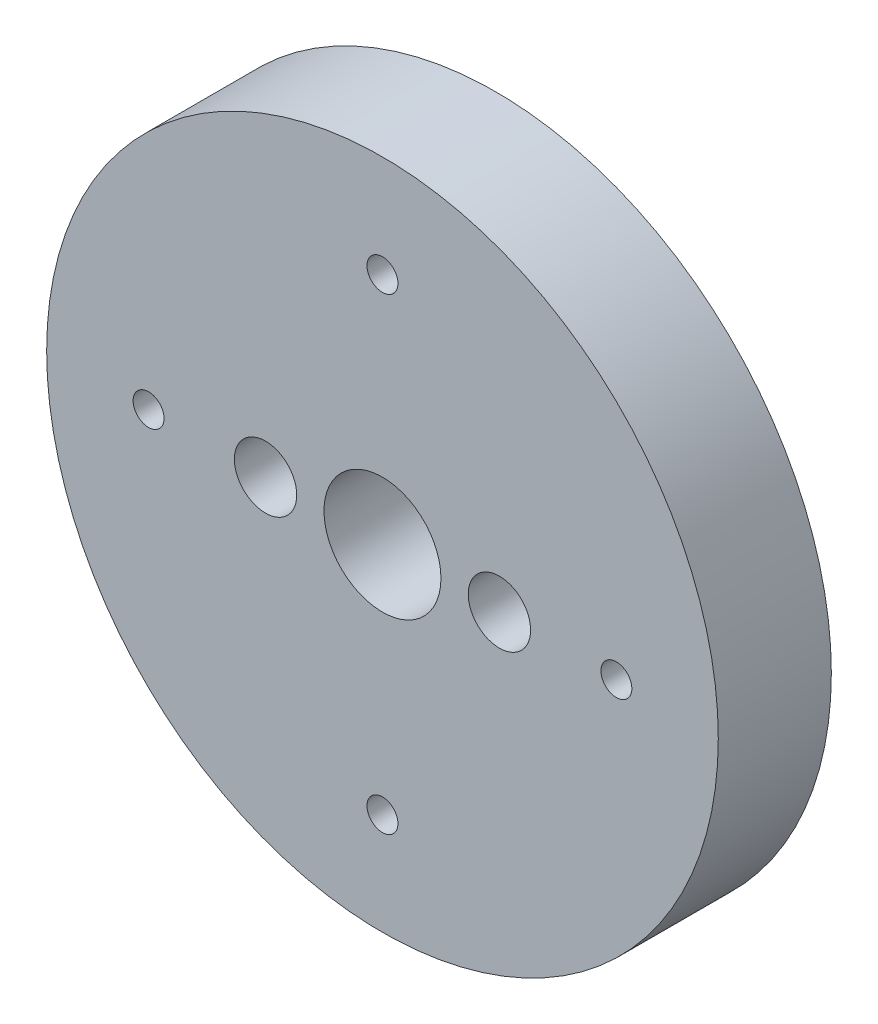
SolidWorks part; units mm, degrees
material "Balsa"
ref_plane "Front Plane" through (0, 0, 0) normal (0, 0, 1) x (1, 0, 0)
ref_plane "Top Plane" through (0, 0, 0) normal (0, 1, 0) x (1, 0, 0)
ref_plane "Right Plane" through (0, 0, 0) normal (1, 0, 0) x (0, 0, -1)
sketch "Sketch1" plane through (0, 0, 0) normal (0, 0, 1) x (1, 0, 0)
  circle A0 centre (0, 0) radius 3
  circle A1 centre (0, 0) radius 17.2292
  dimension "D1" = 6
  dimension "D2" = 34.4583
extrude "Boss-Extrude1" add sketch "Sketch1" along normal blind 5.8
sketch "Sketch2" plane through (0, 0, 5.8) normal (0, 0, 1) x (1, 0, 0)
  line L0 (0, 0) -> (0, 17.2292) construction
  circle A0 centre (0, 0) radius 17.2292 construction
  circle A1 centre (0, 12) radius 0.7937
  circle A2 centre (12, 0) radius 0.7937
  circle A3 centre (0, -12) radius 0.7937
  circle A4 centre (-12, 0) radius 0.7937
  circle A5 centre (0, 0) radius 12 construction
  dimension "D1" = 1.5875
  dimension "D2" = 12
  dimension "D3" = 4
extrude "Cut-Extrude1" cut sketch "Sketch2" against normal through all
hole_wizard "M3 Clearance Hole1" positions "Sketch4" profile "Sketch3" hole size "M3" standard "Ansi Metric"
sketch "Sketch4" plane through (0, 0, 5.8) normal (0, 0, 1) x (1, 0, 0)
  line L0 (0, 0) -> (-6, 0) construction
  line L2 (0, 0) -> (0, 5.7084) construction
  point P9 (-6, 0)
  point P22 (6, 0)
  dimension "D1" = 6
sketch "Sketch3" plane through (-6, 0, 5.8) normal (1, 0, 0) x (0, -1, 0)
  line L0 (0, 0) -> (0, 13.6614)
  line L1 (0, 13.6614) -> (1.6, 12.7)
  line L2 (1.6, 12.7) -> (1.6, 0)
  line L5 (1.6, 0) -> (0, 0)
  line L10 (0, 13.6614) -> (-1.6, 12.7) construction
  line L11 (0, -6.35) -> (0, 107.95) construction
  dimension "Hole Dia." = 3.2
  dimension "Hole Depth" = 12.7
  dimension "Drill Angle" = 118
